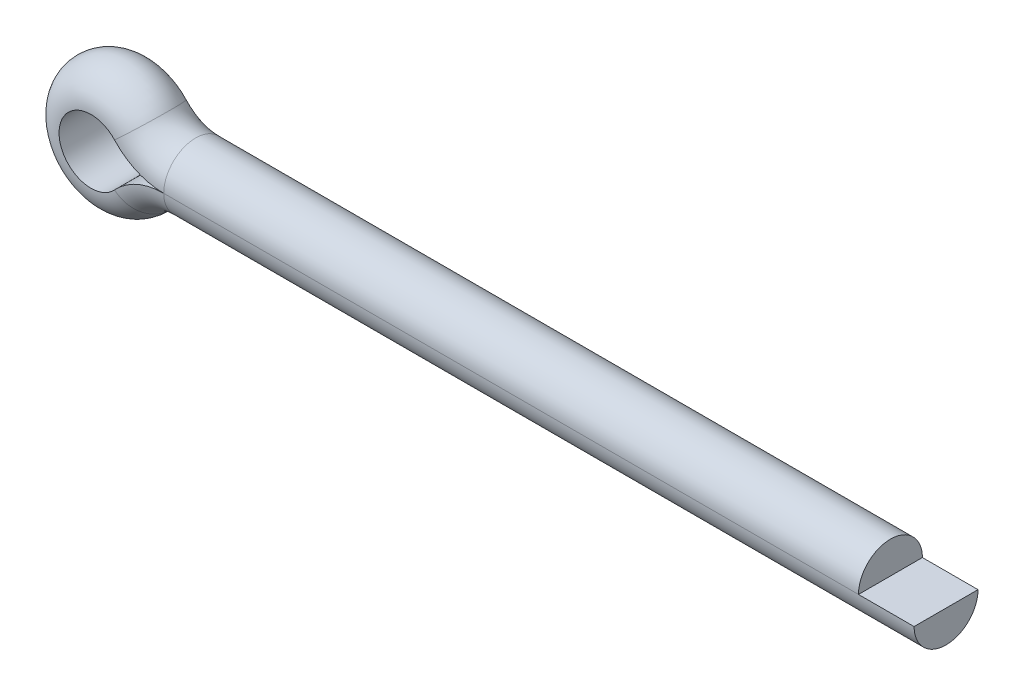
SolidWorks part; units mm, degrees
ref_plane "前视基准面" through (0, 0, 0) normal (0, 0, 1) x (1, 0, 0)
ref_plane "上视基准面" through (0, 0, 0) normal (0, 1, 0) x (1, 0, 0)
ref_plane "右视基准面" through (0, 0, 0) normal (1, 0, 0) x (0, 0, -1)
sketch "草图1" plane through (0, 0, 0) normal (0, 0, 1) x (1, 0, 0)
  line L0 (10.5663, 0) -> (106.8449, 0) construction
  line L1 (-50, 2.3) -> (0, 2.3)
  line L2 (-50, -2.3) -> (4, -2.3)
  arc A0 (-51.8421, 3.1099) -> (-51.8421, -3.1099) centre (-55.2316, 0) ccw
  arc A1 (-50, -2.3) -> (-51.8421, -3.1099) centre (-50, -4.8) ccw
  arc A2 (-50, 2.3) -> (-51.8421, 3.1099) centre (-50, 4.8) cw
  dimension "D1" = 2.5
  dimension "D3" = 4.6
  dimension "D2" = 4.6
  dimension "D4" = 50
  dimension "D5" = 4
sketch "草图2" plane through (0, 0, 0) normal (1, 0, 0) x (0, 0, -1)
  line L0 (-2.3, 0) -> (2.3, 0)
  arc A0 (2.3, 0) -> (-2.3, 0) centre (0, 0) ccw
sweep "扫描1" add profiles "草图2" path "草图1"
